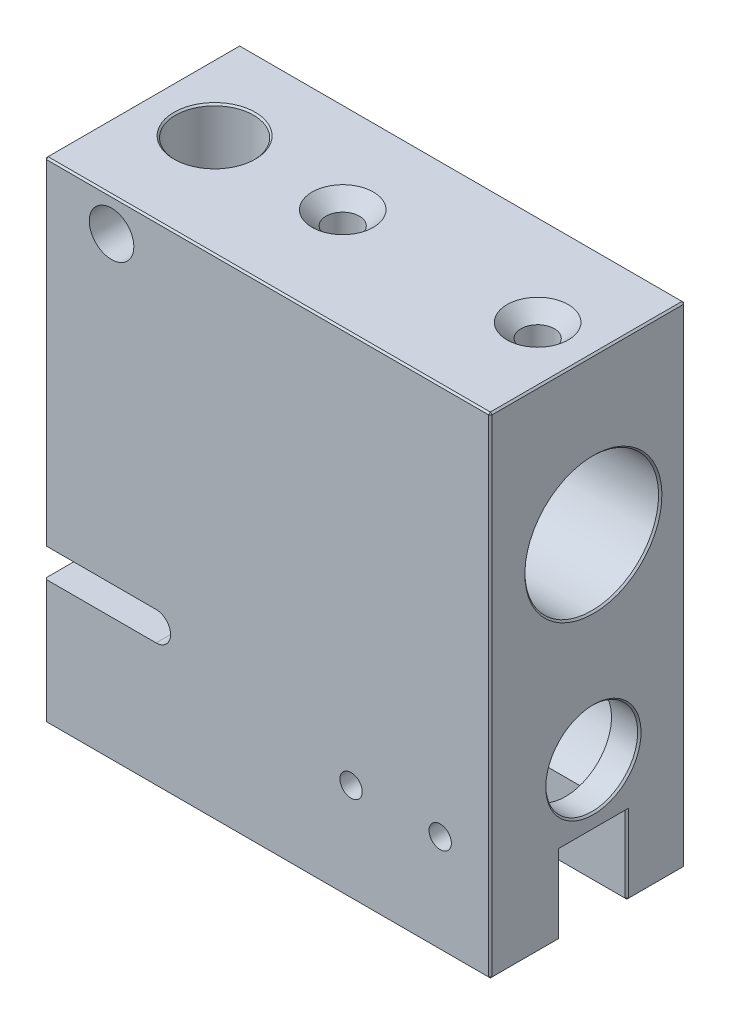
SolidWorks part; units mm, degrees
ref_plane "Plan1" through (0, 0, 0) normal (0, 0, 1) x (1, 0, 0)
ref_plane "Plan2" through (0, 0, 0) normal (0, 1, 0) x (1, 0, 0)
ref_plane "Plan3" through (0, 0, 0) normal (1, 0, 0) x (0, 0, -1)
sketch "Esquisse1" plane through (0, 0, 0) normal (0, 0, 1) x (1, 0, 0)
  line L0 (-40, 44) -> (40, 44)
  line L1 (-40, 44) -> (-40, -44)
  line L2 (40, -44) -> (-40, -44)
  line L3 (40, -44) -> (40, 44)
  point P4 (40, 36)
  dimension "D1" = 88
  dimension "D2" = 44
  dimension "D3" = 80
  dimension "D4" = 40
  dimension "D5" = 8
extrude "Base-Extrusion" add sketch "Esquisse1" along normal blind 35
sketch "Esquisse4" plane through (-40, 0, 0) normal (-1, 0, 0) x (0, 0, 1)
  line L0 (0, 44) -> (0, -44) construction
  line L1 (35, 44) -> (0, 44) construction
  circle A0 centre (16.5, 16) radius 12
  dimension "D2" = 24
  dimension "D1" = 16.5
  dimension "D3" = 28
extrude "Boss.-Extru.2" add sketch "Esquisse4" against normal through all
sketch "Esquisse5" plane through (-40, 0, 0) normal (-1, 0, 0) x (0, 0, 1)
  line L0 (35, 44) -> (35, -44) construction
  circle A0 centre (16.5, 16) radius 12
  dimension "D1" = 18.5
  dimension "D2" = 24
extrude "Enlèv. mat.-Extru.1" cut sketch "Esquisse5" against normal blind 145
sketch "Esquisse6" plane through (40, 0, 0) normal (1, 0, 0) x (0, 0, -1)
  line L1 (-16.5, -48.0139) -> (-16.5, 48.4557) construction
  line L2 (2, 16) -> (-38, 16) construction
  line L3 (-22.5, -44) -> (-22.5, -30)
  line L4 (-35, -44) -> (0, -44) construction
  line L5 (-22.5, -30) -> (-10.5, -30)
  line L6 (-10.5, -30) -> (-10.5, -44)
  line L7 (-10.5, -44) -> (-22.5, -44)
  dimension "D1" = 6
  dimension "D2" = 6
extrude "Enlèv. mat.-Extru.2" cut sketch "Esquisse6" against normal blind 145
sketch "Esquisse12" plane through (-40, 0, 0) normal (-1, 0, 0) x (0, 0, 1)
  line L0 (16.5, 44) -> (16.5, -44) construction
  line L1 (-5, -19) -> (43, -19) construction
  line L2 (10.5, -44) -> (0, -44) construction
  circle A0 centre (16.5, -19) radius 12.75
  dimension "D2" = 25.5
  dimension "D1" = 25
extrude "Enlèv. mat.-Extru.4" cut sketch "Esquisse12" against normal blind 75
sketch "Esquisse13" plane through (35, 0, 0) normal (-1, 0, 0) x (0, 0, 1)
  circle A0 centre (16.5, -19) radius 8.25
  dimension "D1" = 16.5
extrude "Enlèv. mat.-Extru.5" cut sketch "Esquisse13" against normal through all
sketch "Esquisse17" plane through (0, 0, 35) normal (0, 0, 1) x (1, 0, 0)
  line L0 (-44.0286, -19) -> (43.0756, -19) construction
  line L1 (35, -19) -> (-40, -19) construction
  line L2 (-40, -16.4) -> (-20, -16.4)
  line L3 (-40, -16.4) -> (-40, -21.6)
  line L4 (-20, -21.6) -> (-40, -21.6)
  line L5 (-20, -21.6) -> (-20, -16.4)
  line L6 (-40, 44) -> (-40, -44) construction
  dimension "D1" = 5.2
  dimension "D2" = 2.6
extrude "Enlèv. mat.-Extru.9" cut sketch "Esquisse17" against normal blind 10
sketch "Esquisse18" plane through (0, 0, 35) normal (0, 0, 1) x (1, 0, 0)
  line L0 (-43.6474, -19) -> (0, -19) construction
  line L2 (35, -19) -> (-40, -19) construction
  circle A0 centre (-20, -19) radius 2.6
  dimension "D1" = 5.2
extrude "Enlèv. mat.-Extru.10" cut sketch "Esquisse18" against normal blind 10
sketch "Esquisse20" plane through (0, -44, 0) normal (0, -1, 0) x (1, 0, 0)
  line L0 (-10, 43) -> (-10, -7) construction
  line L1 (41.4988, 16.5) -> (-49.1228, 16.5) construction
  line L2 (35, 16.5) -> (-40, 16.5) construction
  line L3 (-4, 3.5) -> (-18, 3.5) construction
  line L4 (-4, 29.5) -> (-18, 29.5) construction
  circle A0 centre (-10, 29.5) radius 2.25
  circle A1 centre (-10, 3.5) radius 2.25
  dimension "D2" = 4.5
  dimension "D1" = 13
extrude "Enlèv. mat.-Extru.12" cut sketch "Esquisse20" against normal blind 14
sketch "Esquisse21" plane through (0, -44, 0) normal (0, -1, 0) x (1, 0, 0)
  line L0 (41.1523, 16.5) -> (-46.1772, 16.5) construction
  line L1 (35, 16.5) -> (-40, 16.5) construction
  circle A0 centre (-10, 3.5) radius 3
  circle A1 centre (-10, 29.5) radius 3
  dimension "D1" = 6
extrude "Enlèv. mat.-Extru.13" cut sketch "Esquisse21" against normal blind 10
chamfer "Chanfrein9" distance 2 angle 30 1 edges at (-10, -30, 5.75)
chamfer "Chanfrein20" distance 2 angle 30 1 edges at (-10, -30, 27.25)
sketch "Esquisse22" plane through (0, 0, 35) normal (0, 0, 1) x (1, 0, 0)
  line L0 (44, -26.25) -> (2, -26.25) construction
  line L2 (31, -18.25) -> (31, -50.25) construction
  line L3 (15, -50.25) -> (15, -19) construction
  line L4 (35, -19) -> (-40, -19) construction
  circle A0 centre (31, -26.25) radius 2
  circle A1 centre (15, -26.25) radius 2
  dimension "D1" = 4
  dimension "D2" = 4
extrude "Enlèv. mat.-Extru.15" cut sketch "Esquisse22" against normal blind 5.5
sketch "Esquisse24" plane through (0, 44, 0) normal (0, 1, 0) x (-1, 0, 0)
  line L0 (28, 37) -> (28, 2) construction
  line L1 (12.5859, 16.5) -> (43.3812, 16.5) construction
  line L2 (-35, 16.5) -> (40, 16.5) construction
  circle A0 centre (28, 16.5) radius 7
  dimension "D1" = 14
extrude "Enlèv. mat.-Extru.23" cut sketch "Esquisse24" against normal blind 25
sketch "Esquisse25" plane through (0, 0, 35) normal (0, 0, 1) x (1, 0, 0)
  line L0 (-28, 44.6957) -> (-28, 13.5487) construction
  line L1 (-28, 28) -> (-28, 44) construction
  line L2 (-38, 38) -> (-17, 38) construction
  circle A0 centre (-28, 38) radius 4
  dimension "D1" = 8
extrude "Enlèv. mat.-Extru.24" cut sketch "Esquisse25" against normal up to next
sketch "Esquisse26" plane through (0, 44, 0) normal (0, 1, 0) x (-1, 0, 0)
  line L0 (-41.9084, 16.5) -> (42.9795, 16.5) construction
  line L2 (-35, 16.5) -> (40, 16.5) construction
  line L3 (5, 25) -> (5, 9) construction
  line L4 (-30, 26) -> (-30, 3.75) construction
  line L5 (-35, 3.75) -> (40, 3.75) construction
  circle A0 centre (-30, 16.5) radius 2.5
  circle A1 centre (5, 16.5) radius 2.5
  dimension "D1" = 5
  dimension "D2" = 5
extrude "Enlèv. mat.-Extru.25" cut sketch "Esquisse26" against normal blind 15
sketch "Esquisse28" plane through (0, 44, 0) normal (0, 1, 0) x (-1, 0, 0)
  circle A0 centre (-30, 16.5) radius 3
  circle A1 centre (5, 16.5) radius 3
  dimension "D1" = 6
  dimension "D2" = 6
extrude "Enlèv. mat.-Extru.26" cut sketch "Esquisse28" against normal blind 12
chamfer "Chanfrein27" distance 2.5 angle 45 2 edges at (27, 44, 16.5) (-8, 44, 16.5)
chamfer "Chanfrein29" distance 0.3 angle 45 29 edges at (40, 0, 35) (-35, 44, 16.5) (0, 44, 35) (40, 4, 16.5) (-40, 16, 28.5) (40, -44, 5.25) (-40, -44, 5.25) (0, -44, 10.5) (0, -44, 22.5) (40, -37, 22.5) (40, -30, 16.5) (40, -37, 10.5) (-40, -37.125, 22.5) (-40, 13.8, 35) (-40, -37.125, 10.5) (0, 44, 0) (-40, -26.6459, 26.7031) (40, 0, 0) (0, -44, 0) (40, -19, 24.75) (-40, 0, 0) (-40, -8.7969, 8.8541) (-40, -32.8, 35) (-40, -16.4, 31.991) (0, -44, 35) (-40, 44, 17.5) (40, 44, 17.5) (40, -44, 28.75) (-40, -44, 28.75)
sketch "Esquisse29" plane through (40, 0, 0) normal (1, 0, 0) x (0, 0, -1)
  line L0 (-16.5, 16) -> (-16.5, 86.1619) construction
  line L1 (-16.5, 63.9994) -> (-16.5, -52)
  line L2 (-16.5, -52) -> (-67.7989, -52)
  line L3 (-67.7989, -52) -> (-67.7989, 63.9994)
  line L4 (-67.7989, 63.9994) -> (-16.5, 63.9994)
